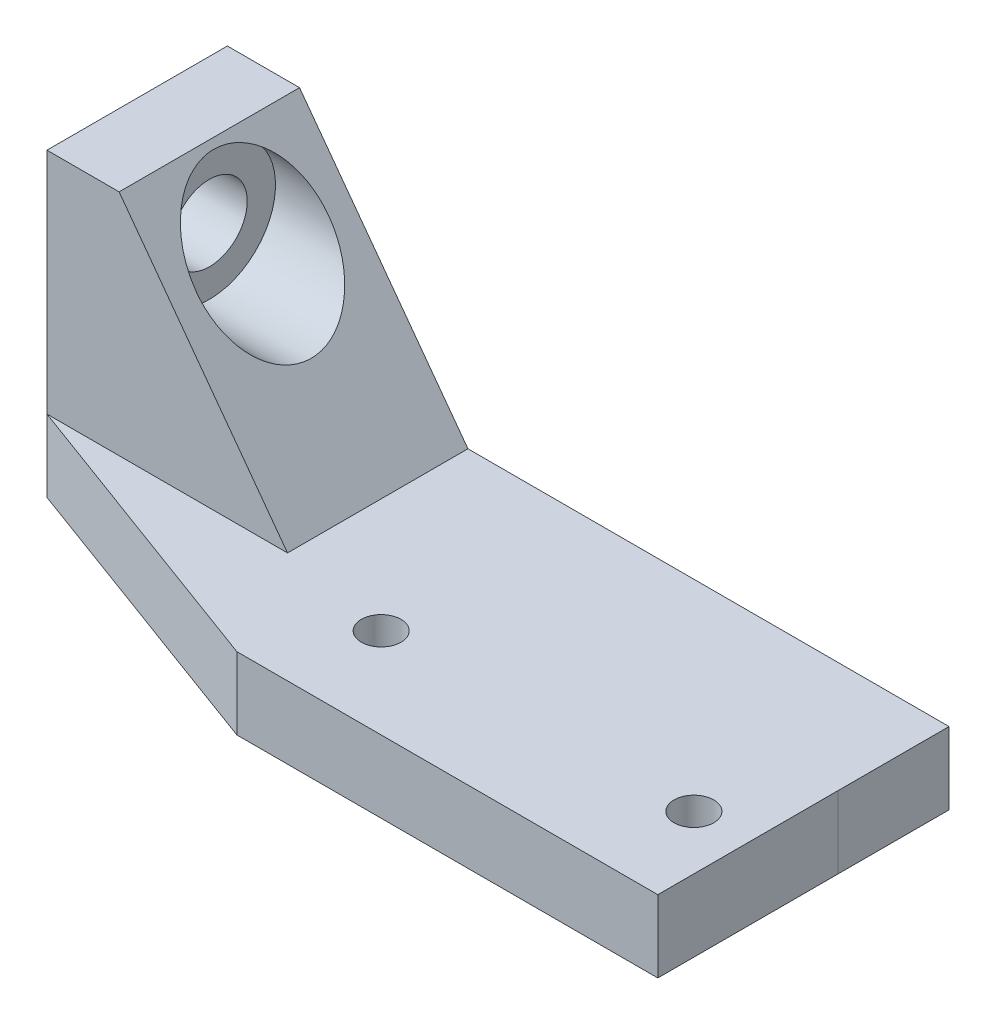
SolidWorks part; units mm, degrees
ref_plane "Front Plane" through (0, 0, 0) normal (0, 0, 1) x (1, 0, 0)
ref_plane "Top Plane" through (0, 0, 0) normal (0, 1, 0) x (1, 0, 0)
ref_plane "Right Plane" through (0, 0, 0) normal (1, 0, 0) x (0, 0, -1)
sketch "Sketch1" plane through (0, 0, 0) normal (0, 1, 0) x (1, 0, 0)
  line L0 (-55, 0) -> (55, 0) construction
  line L1 (-17.5, 7.5) -> (17.5, 7.5)
  line L2 (-17.5, 7.5) -> (-17.5, -7.5)
  line L3 (-17.5, -7.5) -> (17.5, -7.5)
  line L4 (17.5, 7.5) -> (17.5, -7.5)
  line L5 (-17.5, 7.5) -> (17.5, -7.5) construction
  line L6 (-17.5, -7.5) -> (17.5, 7.5) construction
  line L7 (0, 17.2835) -> (0, -22.1632) construction
  line L8 (0, -55) -> (0, 55) construction
  line L9 (-42.4986, 1.7117) -> (-17.5, -7.5)
  line L10 (-42.4986, -15) -> (-42.4986, 259) construction
  line L13 (-42.4986, 16.7117) -> (-42.4986, 1.7117)
  line L14 (-42.4986, 16.7117) -> (17.5014, 16.7117)
  line L15 (17.5014, -15) -> (17.5014, 83.6143) construction
  line L16 (17.5014, 16.7117) -> (17.5, 7.5)
  line L17 (17.5, 7.5) -> (-4.1161, 7.5)
  circle A0 centre (-13, 0) radius 1.65
  circle A1 centre (13, 0) radius 1.65
  point P0 (0, 0)
  dimension "D2" = 3.3
  dimension "D1" = 15
  dimension "D3" = 26
  dimension "D4" = 35
  dimension "D6" = 15
extrude "Boss-Extrude1" add sketch "Sketch1" along normal blind 6
sketch "Sketch2" plane through (-42.4986, 0, 0) normal (-1, 0, 0) x (0, 0, 1)
  line L3 (-16.7117, 25) -> (-1.7117, 25)
  line L5 (-9.2117, 24.0579) -> (-9.2117, 11.1879) construction
  line L6 (-16.7117, 0) -> (-1.7117, 0) construction
  line L8 (-16.7117, 0) -> (-1.7117, 0)
  line L10 (-1.7117, 25) -> (-1.7117, 0)
  line L11 (-16.7117, 25) -> (-16.7117, 0)
  circle A0 centre (-9.2117, 19) radius 3.15
  dimension "D2" = 6.3
  dimension "D1" = 25
  dimension "D3" = 19
  dimension "D4" = 15
extrude "Boss-Extrude2" add sketch "Sketch2" against normal blind 20
sketch "Sketch4" plane through (0, 0, -1.7117) normal (0, 0, 1) x (1, 0, 0)
  line L0 (-36.4986, 25) -> (-22.4986, 6)
  line L1 (-22.4986, 25) -> (-42.4986, 25) construction
  line L2 (-42.4986, 6) -> (-17.5, 6) construction
  line L3 (-22.4986, 6) -> (-22.4986, 25)
  line L4 (-22.4986, 25) -> (-36.4986, 25)
  line L5 (-42.4986, 96) -> (-42.4986, -84) construction
  dimension "D1" = 6
extrude "Cut-Extrude1" cut sketch "Sketch4" against normal through all
ref_plane "Plane1" through (-36.4986, 0, 0) normal (-1, 0, 0) x (0, 0, 1)
sketch "Sketch5" plane through (-36.4986, 0, 0) normal (-1, 0, 0) x (0, 0, 1)
  circle A0 centre (-9.2117, 19) radius 5.5
  dimension "D1" = 11
extrude "Cut-Extrude2" cut sketch "Sketch5" against normal through all
